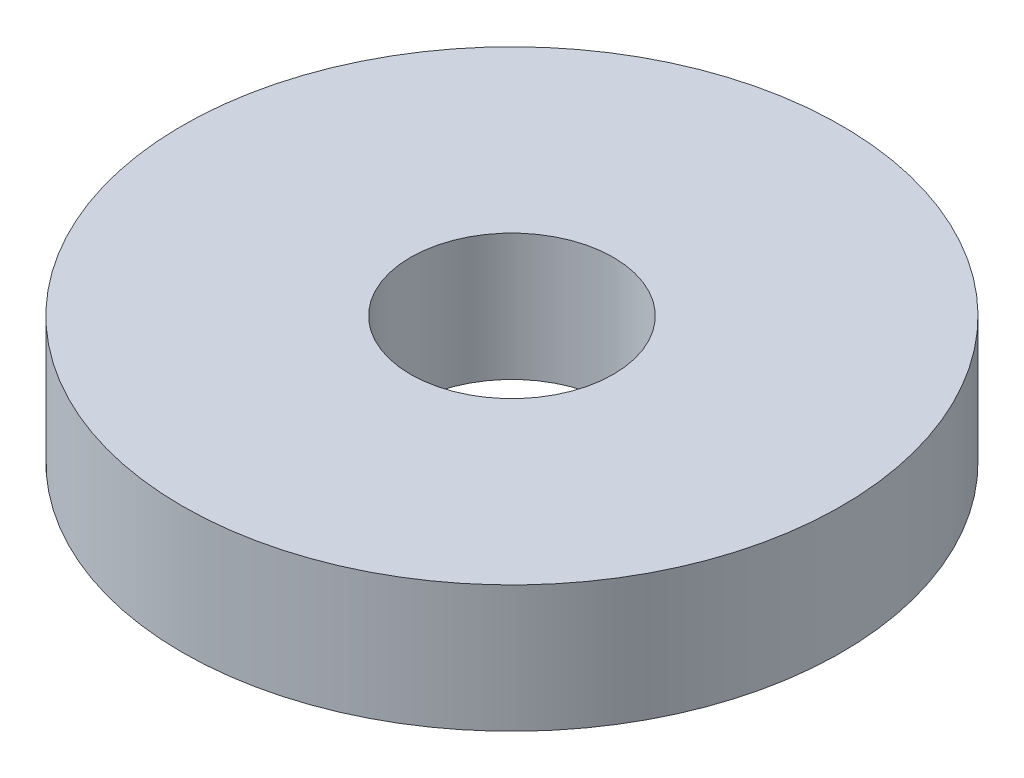
SolidWorks part; units mm, degrees
material "强力钕磁铁"
ref_plane "前视基准面" through (0, 0, 0) normal (0, 0, 1) x (1, 0, 0)
ref_plane "上视基准面" through (0, 0, 0) normal (0, 1, 0) x (1, 0, 0)
ref_plane "右视基准面" through (0, 0, 0) normal (1, 0, 0) x (0, 0, -1)
sketch "草图1" plane through (0, 0, 0) normal (0, 1, 0) x (1, 0, 0)
  circle A0 centre (0, 0) radius 20
  circle A1 centre (0, 0) radius 65
  dimension "D1" = 130
  dimension "D2" = 40
extrude "凸台-拉伸1" add sketch "草图1" along normal blind 25
